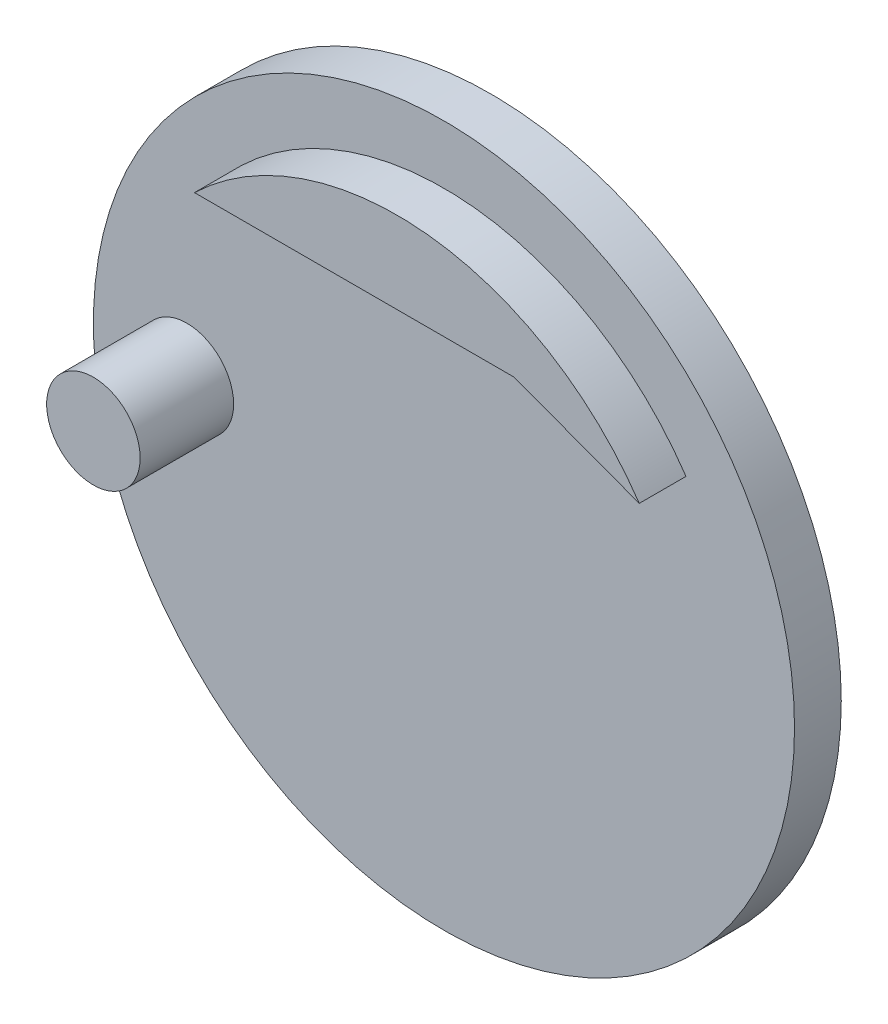
SolidWorks part; units mm, degrees
ref_plane "Front Plane" through (0, 0, 0) normal (0, 0, 1) x (1, 0, 0)
ref_plane "Top Plane" through (0, 0, 0) normal (0, 1, 0) x (1, 0, 0)
ref_plane "Right Plane" through (0, 0, 0) normal (1, 0, 0) x (0, 0, -1)
sketch "Sketch1" plane through (0, 0, 0) normal (0, 0, 1) x (1, 0, 0)
  circle A0 centre (0, 0) radius 37.5
  dimension "D1" = 75
extrude "Boss-Extrude1" add sketch "Sketch1" along normal blind 5
ref_plane "Plane1" through (0, 0, 5) normal (0, 0, 1) x (1, 0, 0)
sketch "Sketch3" plane through (0, 0, 5) normal (0, 0, 1) x (1, 0, 0)
  line L0 (25.8904, 17.5) -> (12.5, 22.5)
  line L1 (12.5, 22.5) -> (-21.6867, 22.5)
  arc A0 (-21.6867, 22.5) -> (25.8904, 17.5) centre (0, 0) cw
  dimension "D1" = 31.25
  dimension "D2" = 22.5
  dimension "D3" = 17.5
  dimension "D4" = 12.5
extrude "Boss-Extrude2" add sketch "Sketch3" along normal blind 5
sketch "Sketch4" plane through (0, 0, 5) normal (0, 0, 1) x (1, 0, 0)
  circle A0 centre (-27.5, 0) radius 5
  point P2 (-9.1843, 0)
  dimension "D1" = 10
  dimension "D2" = 27.5
extrude "Boss-Extrude3" add sketch "Sketch4" along normal blind 10
